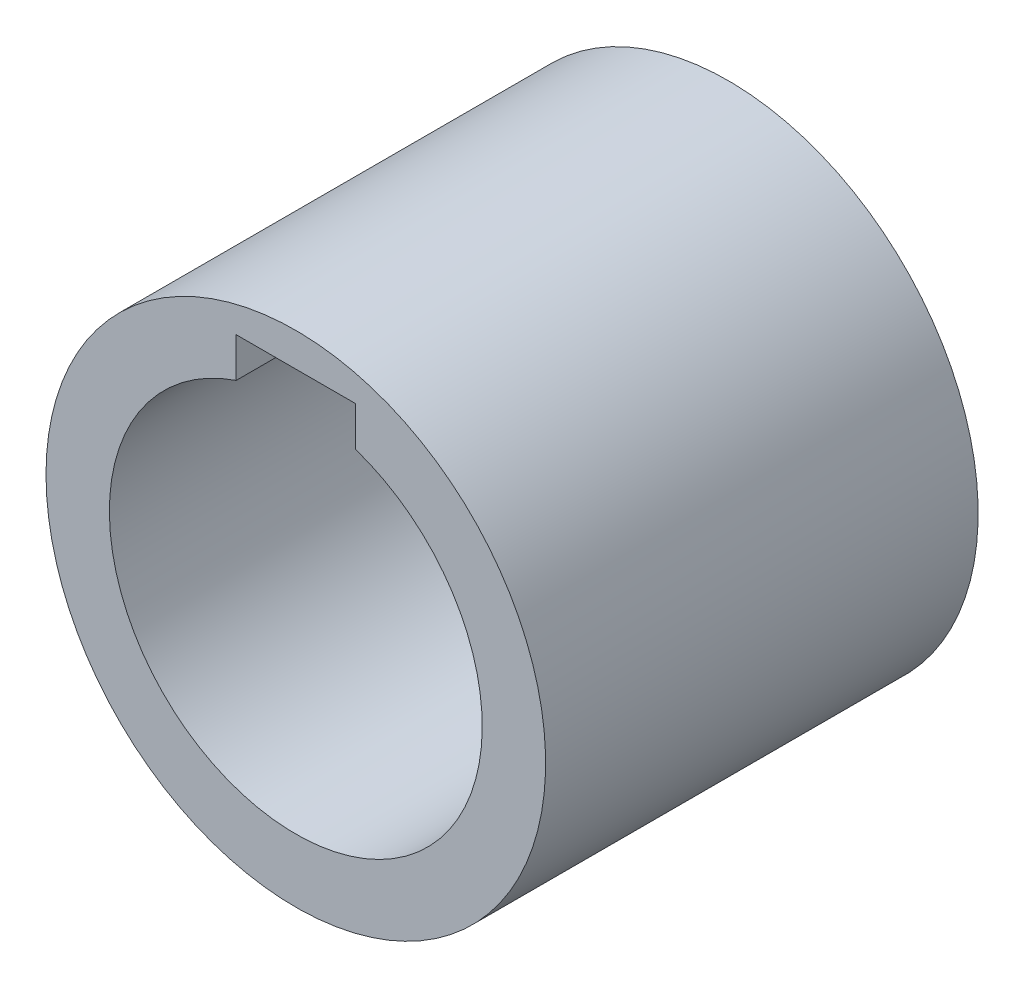
SolidWorks part; units mm, degrees
ref_plane "Front Plane" through (0, 0, 0) normal (0, 0, 1) x (1, 0, 0)
ref_plane "Top Plane" through (0, 0, 0) normal (0, 1, 0) x (1, 0, 0)
ref_plane "Right Plane" through (0, 0, 0) normal (1, 0, 0) x (0, 0, -1)
sketch "Sketch1" plane through (0, 0, 0) normal (0, 0, 1) x (1, 0, 0)
  circle A0 centre (0, 0) radius 16.75
  circle A1 centre (0, 0) radius 12.5
extrude "Boss-Extrude1" add sketch "Sketch1" along normal blind 29
sketch "Sketch2" plane through (0, 0, 29) normal (0, 0, 1) x (1, 0, 0)
  line L1 (-4, 14.5) -> (4, 14.5)
  line L2 (-4, 14.5) -> (-4, 10.5)
  line L3 (-4, 10.5) -> (4, 10.5)
  line L4 (4, 14.5) -> (4, 10.5)
  line L5 (-4, 14.5) -> (4, 10.5) construction
  line L6 (-4, 10.5) -> (4, 14.5) construction
  circle A0 centre (0, 0) radius 12.5 construction
  point P0 (0, 12.5)
  dimension "D1" = 8
  dimension "D2" = 4
extrude "Cut-Extrude2" cut sketch "Sketch2" against normal blind 25.5
fillet "Fillet1" radius 2.5 1 edges at (4, 13.1714, 3.5)
fillet "Fillet2" radius 2.5 1 edges at (-4, 13.1714, 3.5)
